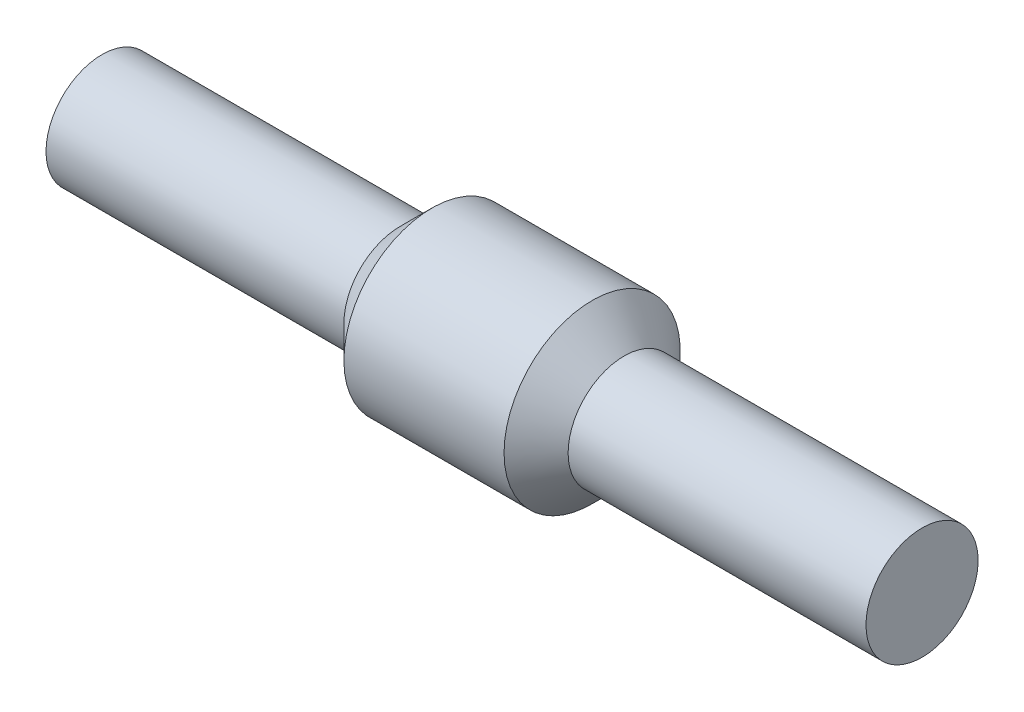
SolidWorks part; units mm, degrees
ref_plane "Front Plane" through (0, 0, 0) normal (0, 0, 1) x (1, 0, 0)
ref_plane "Top Plane" through (0, 0, 0) normal (0, 1, 0) x (1, 0, 0)
ref_plane "Right Plane" through (0, 0, 0) normal (1, 0, 0) x (0, 0, -1)
sketch "Sketch1" plane through (0, 0, 0) normal (0, 0, 1) x (1, 0, 0)
  line L0 (-20, 0) -> (20, 0) construction
  dimension "D1" = 40
sketch "Sketch2" plane through (0, 0, 0) normal (0, 0, 1) x (1, 0, 0)
  line L0 (12.8, 0) -> (12.8, 1.75)
  line L1 (-20, 0) -> (20, 0) construction
  line L2 (12.8, 1.75) -> (3.5, 1.75)
  line L3 (3.5, 1.75) -> (2.5, 2.75)
  line L4 (2.5, 2.75) -> (0, 2.75)
  line L5 (0, 2.75) -> (0, 0)
  line L6 (0, 0) -> (12.8, 0)
  dimension "D1" = 10.3
  dimension "D2" = 2.75
  dimension "D3" = 1
  dimension "D4" = 7.2
  dimension "D5" = 45
revolve "Revolve1" add sketch "Sketch2" angle 360 about L0
mirror "Mirror1" about plane through (0, 0, 0) normal (1, 0, 0) of "Revolve1"
equation "\"end to end\" = 40"
equation "\"D1@Sketch1\"=\"end to end\""
